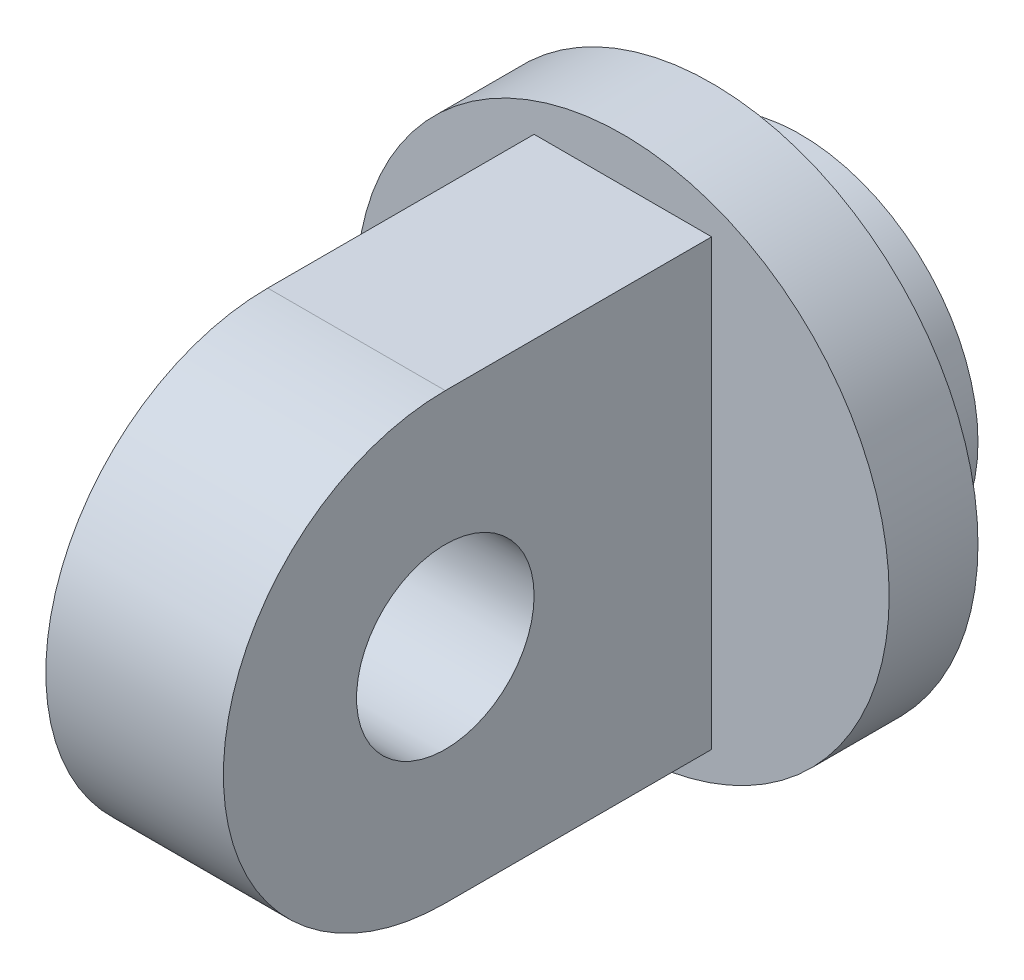
SolidWorks part; units mm, degrees
material "Plain Carbon Steel"
ref_plane "Front Plane" through (0, 0, 0) normal (0, 0, 1) x (1, 0, 0)
ref_plane "Top Plane" through (0, 0, 0) normal (0, 1, 0) x (1, 0, 0)
ref_plane "Right Plane" through (0, 0, 0) normal (1, 0, 0) x (0, 0, -1)
sketch "Sketch1" plane through (0, 0, 0) normal (0, 0, 1) x (1, 0, 0)
  circle A1 centre (0, 0) radius 500
  dimension "D2" = 1000
extrude "Boss-Extrude1" add sketch "Sketch1" along normal blind 250
sketch "Sketch3" plane through (0, 0, 0) normal (0, 0, -1) x (-1, 0, 0)
  circle A0 centre (0, 0) radius 125
  dimension "D1" = 250
extrude "Cut-Extrude1" cut sketch "Sketch3" against normal blind 100
sketch "Sketch4" plane through (0, 0, 250) normal (0, 0, 1) x (1, 0, 0)
  circle A0 centre (0, 0) radius 750
  dimension "D1" = 1500
extrude "Boss-Extrude2" add sketch "Sketch4" along normal blind 250
sketch "Sketch5" plane through (0, 0, 0) normal (1, 0, 0) x (0, 0, -1)
  line L2 (0, 0) -> (-2325.9915, 0) construction
  line L3 (-1250, 625) -> (-500, 625)
  line L4 (-500, 625) -> (-500, -625)
  line L5 (-500, -625) -> (-1250, -625)
  arc A0 (-1250, 625) -> (-1250, -625) centre (-1250, 0) ccw
  circle A1 centre (-1250, 0) radius 250
  dimension "D2" = 750
  dimension "D3" = 625
  dimension "D4" = 625
  dimension "D1" = 500
extrude "Boss-Extrude4" add sketch "Sketch5" along normal mid plane 500
